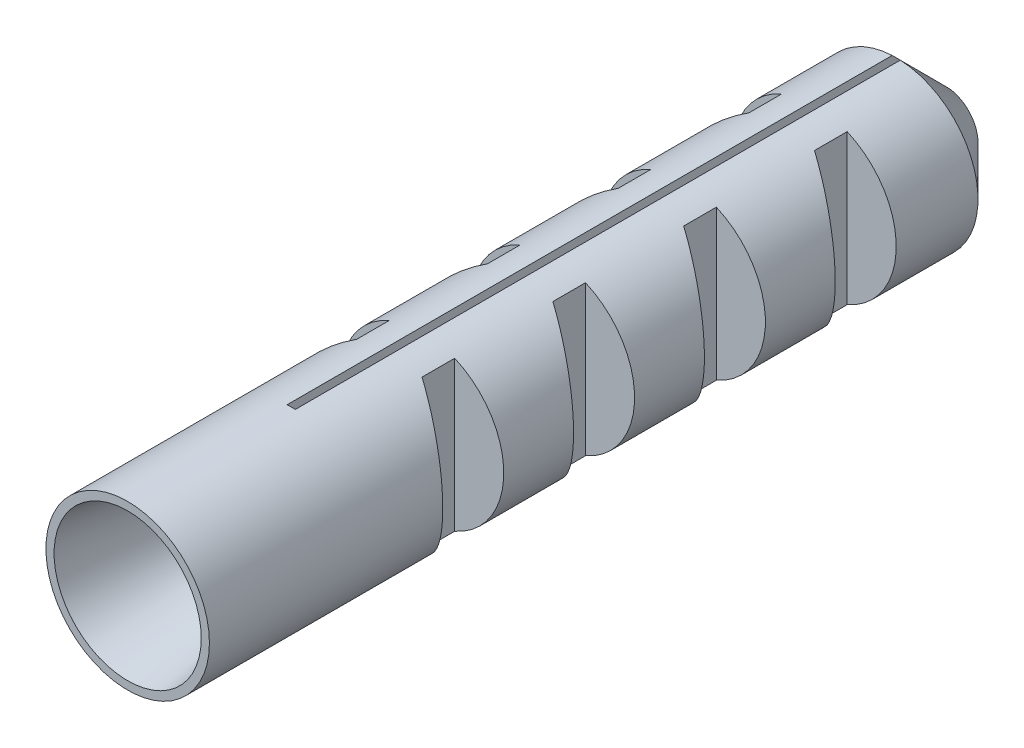
SolidWorks part; units mm, degrees
ref_plane "Front Plane" through (0, 0, 0) normal (0, 0, 1) x (1, 0, 0)
ref_plane "Top Plane" through (0, 0, 0) normal (0, 1, 0) x (1, 0, 0)
ref_plane "Right Plane" through (0, 0, 0) normal (1, 0, 0) x (0, 0, -1)
sketch "Sketch1" plane through (0, 0, 0) normal (0, 0, 1) x (1, 0, 0)
  circle A0 centre (0, 0) radius 5
  dimension "D1" = 10
extrude "Boss-Extrude1" add sketch "Sketch1" along normal blind 50
sketch "Sketch2" plane through (0, 0, 0) normal (0, 1, 0) x (1, 0, 0)
  line L0 (5, 0) -> (-5, 0) construction
  line L1 (0.25, 0) -> (-0.25, 0)
  line L2 (0.25, 0) -> (0.25, -40)
  line L3 (0.25, -40) -> (-0.25, -40)
  line L4 (-0.25, 0) -> (-0.25, -40)
  line L5 (-5, -8) -> (-2, -8)
  line L6 (-5, 0) -> (-5, -50) construction
  line L7 (-2, -8) -> (-2, -10)
  line L8 (-2, -10) -> (-5, -11.7321)
  line L9 (-5, -11.7321) -> (-5, -8)
  line L10 (0, 0.4454) -> (0, -51.5755) construction
  line L11 (2, -10) -> (5, -11.7321)
  line L12 (2, -8) -> (2, -10)
  line L13 (5, -11.7321) -> (5, -8)
  line L14 (5, -8) -> (2, -8)
  line L15 (-5, -16) -> (-2, -16)
  line L16 (-5, -19.7321) -> (-5, -16)
  line L17 (-2, -16) -> (-2, -18)
  line L18 (-2, -18) -> (-5, -19.7321)
  line L19 (2, -16) -> (2, -18)
  line L20 (5, -16) -> (2, -16)
  line L21 (2, -18) -> (5, -19.7321)
  line L22 (5, -19.7321) -> (5, -16)
  line L23 (-5, -24) -> (-2, -24)
  line L24 (-5, -27.7321) -> (-5, -24)
  line L25 (-2, -24) -> (-2, -26)
  line L26 (-2, -26) -> (-5, -27.7321)
  line L27 (2, -24) -> (2, -26)
  line L28 (5, -24) -> (2, -24)
  line L29 (2, -26) -> (5, -27.7321)
  line L30 (5, -27.7321) -> (5, -24)
  line L31 (-5, -32) -> (-2, -32)
  line L32 (-5, -35.7321) -> (-5, -32)
  line L33 (-2, -32) -> (-2, -34)
  line L34 (-2, -34) -> (-5, -35.7321)
  line L35 (2, -32) -> (2, -34)
  line L36 (5, -32) -> (2, -32)
  line L37 (2, -34) -> (5, -35.7321)
  line L38 (5, -35.7321) -> (5, -32)
  point P6 (0, 0)
  dimension "D1" = 40
  dimension "D2" = 0.5
  dimension "D3" = 60
  dimension "D4" = 2
  dimension "D5" = 3
  dimension "D6" = 8
  dimension "D7" = 4
extrude "Cut-Extrude1" cut sketch "Sketch2" against normal through all both and the other way through all
chamfer "Chamfer1" distance 3 angle 45 2 edges at (5, 0, 0) (-5, 0, 0)
sketch "Sketch3" plane through (0, 0, 50) normal (0, 0, 1) x (1, 0, 0)
  circle A0 centre (0, 0) radius 4.5
  dimension "D1" = 9
extrude "Cut-Extrude2" cut sketch "Sketch3" against normal blind 50 draft 10
